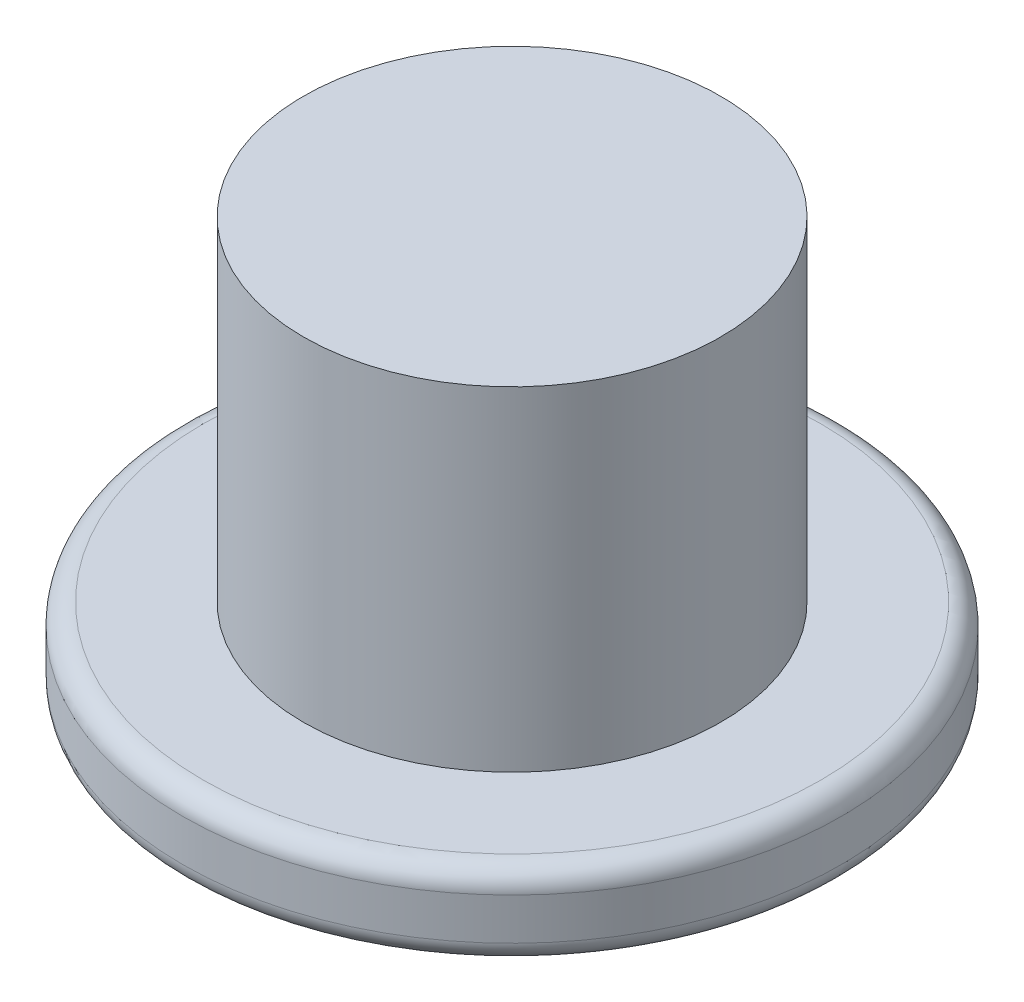
SolidWorks part; units mm, degrees
ref_plane "Front Plane" through (0, 0, 0) normal (0, 0, 1) x (1, 0, 0)
ref_plane "Top Plane" through (0, 0, 0) normal (0, 1, 0) x (1, 0, 0)
ref_plane "Right Plane" through (0, 0, 0) normal (1, 0, 0) x (0, 0, -1)
sketch "Sketch1" plane through (0, 0, 0) normal (0, 1, 0) x (1, 0, 0)
  circle A4 centre (-5.4087, -40.3067) radius 7.9
  circle A12 centre (-5.4087, -40.3067) radius 4.9321
  dimension "D5" = 15.8
extrude "Boss-Extrude5" add sketch "Sketch1" along normal blind 2 contours A4
sketch "Sketch4" plane through (0, 2, 0) normal (0, 1, 0) x (1, 0, 0)
  circle A0 centre (-5.4087, -40.3067) radius 5
  circle A1 centre (-5.4087, -40.3067) radius 7.9 construction
extrude "Boss-Extrude6" add sketch "Sketch4" along normal blind 8
sketch "Sketch5" plane through (0, 0, 0) normal (0, -1, 0) x (1, 0, 0)
  text T0 "10" font "Comic Sans MS" height 7.5
  point P1 (-5.4087, 25.1919)
  point P2 (0, 0)
  point P3 (-9.5758, 36.1339)
extrude "Cut-Extrude2" cut sketch "Sketch5" against normal blind 0.5
fillet "Fillet1" radius 0.5 2 edges at (-5.4087, 2, 48.2067) (-5.4087, 0, 48.2067)
